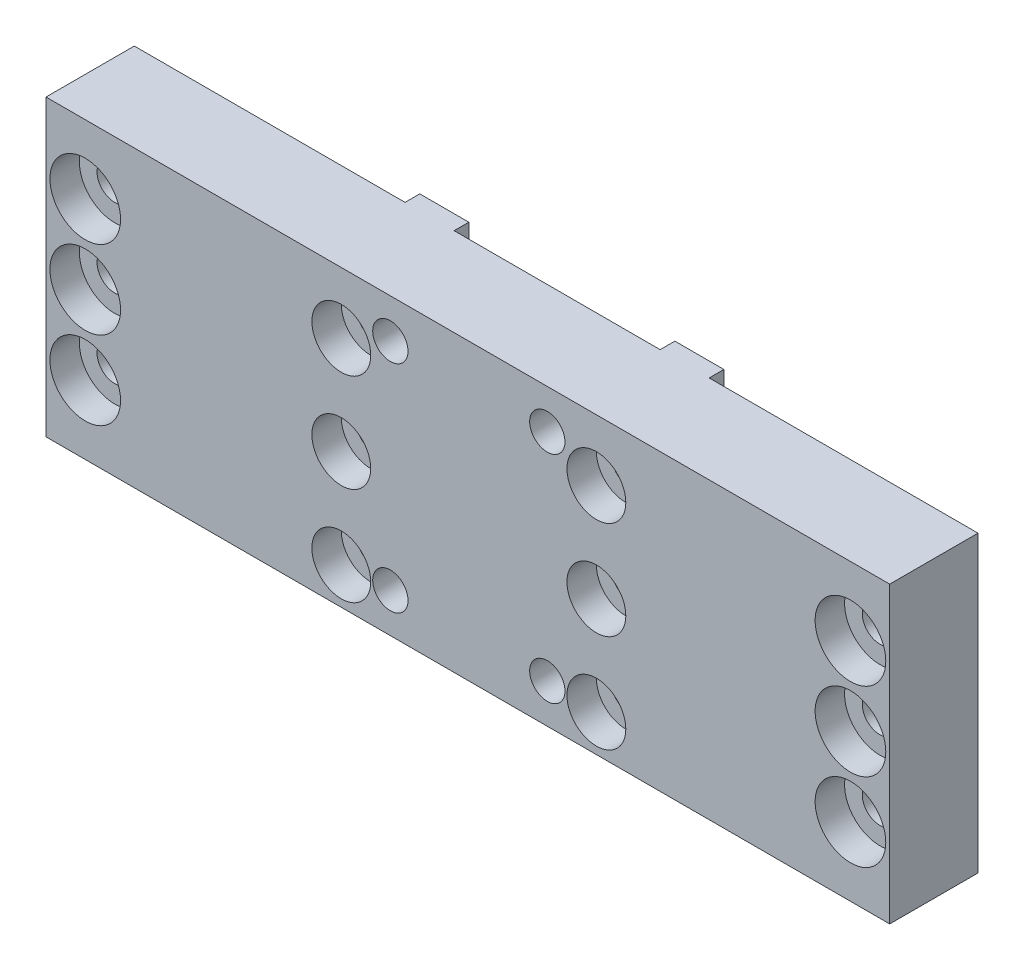
SolidWorks part; units mm, degrees
material "ABS"
ref_plane "前基準面" through (0, 0, 0) normal (0, 0, 1) x (1, 0, 0)
ref_plane "上基準面" through (0, 0, 0) normal (0, 1, 0) x (1, 0, 0)
ref_plane "右基準面" through (0, 0, 0) normal (1, 0, 0) x (0, 0, -1)
sketch "草圖1" plane through (0, 0, 0) normal (0, 0, 1) x (1, 0, 0)
  line L1 (0, 0) -> (70, 0)
  line L2 (0, 0) -> (0, 30)
  line L3 (0, 30) -> (70, 30)
  line L4 (70, 0) -> (70, 30)
  dimension "D1" = 70
  dimension "D2" = 30
extrude "填料-伸長1" add sketch "草圖1" along normal blind 9
sketch "草圖2" plane through (0, 0, 0) normal (-1, 0, 0) x (0, 0, 1)
  line L0 (9, 30) -> (9, 0) construction
  line L1 (9, 30) -> (-103.1, 30)
  line L2 (9, 30) -> (9, 0)
  line L3 (9, 0) -> (-103.1, 0)
  line L4 (-103.1, 30) -> (-103.1, 0)
  dimension "D1" = 30
  dimension "D2" = 112.1
extrude "填料-伸長2" add sketch "草圖2" along normal blind 8
sketch "草圖3" plane through (70, 0, 0) normal (1, 0, 0) x (0, 0, -1)
  line L5 (-9, 30) -> (33.6, 30)
  line L6 (-9, 30) -> (-9, 0)
  line L7 (-9, 0) -> (33.6, 0)
  line L8 (33.6, 30) -> (33.6, 0)
  dimension "D1" = 42.6
extrude "填料-伸長3" add sketch "草圖3" along normal blind 8
sketch "草圖5" plane through (0, 0, -33.6) normal (0, 0, -1) x (-1, 0, 0)
  line L5 (-78, 30) -> (-59.5, 30)
  line L6 (-78, 30) -> (-78, 0)
  line L11 (-78, 0) -> (-59.5, 0)
  line L12 (-59.5, 30) -> (-59.5, 0)
  circle A6 centre (-65.75, 26) radius 2
  circle A7 centre (-65.75, 18) radius 2
  circle A8 centre (-65.75, 10) radius 2
  dimension "D3" = 8
  dimension "D1" = 18.5
  dimension "D2" = 30
  dimension "D4" = 8
  dimension "D5" = 10
  dimension "D6" = 6.25
  dimension "D7" = 6.25
  dimension "D8" = 6.25
extrude "填料-伸長4" add sketch "草圖5" along normal blind 5.5
sketch "草圖11" plane through (-8, 0, 0) normal (-1, 0, 0) x (0, 0, 1)
  line L0 (9, 30) -> (-103.1, 30) construction
  line L2 (9, 0) -> (9, 30) construction
  circle A0 centre (-23, 23) radius 2
  circle A1 centre (-23, 15) radius 2
  circle A2 centre (-23, 7) radius 2
  circle A3 centre (-15, 23) radius 2
  circle A4 centre (-15, 15) radius 2
  circle A5 centre (-15, 7) radius 2
  circle A6 centre (-7, 23) radius 2
  circle A7 centre (-7, 15) radius 2
  circle A8 centre (-7, 7) radius 2
  dimension "D1" = 8
  dimension "D6" = 4
  dimension "D2" = 8
  dimension "D3" = 7
  dimension "D4" = 16
  dimension "D5" = 3
extrude "除料-伸長4" cut sketch "草圖11" against normal blind 8
sketch "草圖12" plane through (0, 0, -103.1) normal (0, 0, -1) x (-1, 0, 0)
  line L0 (8, 30) -> (0, 30) construction
  line L2 (0, 30) -> (0, 0) construction
  circle A0 centre (3, 23) radius 1.8
  circle A1 centre (3, 15) radius 1.8
  circle A2 centre (3, 7) radius 1.8
  dimension "D1" = 8
  dimension "D5" = 3.6
  dimension "D6" = 3.6
  dimension "D7" = 3.6
  dimension "D2" = 8
  dimension "D3" = 7
  dimension "D4" = 3
extrude "除料-伸長6" cut sketch "草圖12" against normal blind 8
sketch "草圖13" plane through (78, 0, 0) normal (1, 0, 0) x (0, 0, -1)
  line L0 (39.1, 30) -> (39.1, 0) construction
  circle A3 centre (9.1, 23) radius 2
  circle A4 centre (9.1, 15) radius 2
  circle A5 centre (9.1, 7) radius 2
  circle A6 centre (17.1, 23) radius 2
  circle A7 centre (17.1, 15) radius 2
  circle A8 centre (17.1, 7) radius 2
  circle A9 centre (25.1, 23) radius 2
  circle A10 centre (25.1, 15) radius 2
  circle A11 centre (25.1, 7) radius 2
  dimension "D1" = 8
  dimension "D2" = 8
  dimension "D3" = 8
  dimension "D4" = 8
  dimension "D6" = 8
  dimension "D5" = 8
  dimension "D7" = 14
  dimension "D8" = 8
  dimension "D9" = 8
extrude "除料-伸長7" cut sketch "草圖13" against normal blind 8
sketch "草圖14" plane through (-8, 0, 0) normal (-1, 0, 0) x (0, 0, 1)
  line L1 (9, 30) -> (-103.1, 30) construction
  line L2 (-103.1, 30) -> (-103.1, 0) construction
  circle A0 centre (-85.1, 23) radius 2
  circle A1 centre (-85.1, 15) radius 2
  circle A2 centre (-85.1, 7) radius 2
  circle A3 centre (-77.1, 23) radius 2
  circle A4 centre (-77.1, 15) radius 2
  circle A5 centre (-77.1, 7) radius 2
  circle A6 centre (-69.1, 23) radius 2
  circle A7 centre (-69.1, 15) radius 2
  circle A8 centre (-69.1, 7) radius 2
  circle A9 centre (-61.1, 23) radius 2
  circle A10 centre (-61.1, 15) radius 2
  circle A11 centre (-61.1, 7) radius 2
  dimension "D1" = 8
  dimension "D6" = 4
  dimension "D2" = 8
  dimension "D3" = 7
  dimension "D5" = 18
  dimension "D4" = 4
extrude "除料-伸長8" cut sketch "草圖14" against normal blind 10
sketch "草圖19" plane through (0, 30, 0) normal (0, 1, 0) x (1, 0, 0)
  line L3 (19.6, 0) -> (24.6, 0)
  line L8 (45.6, 0) -> (50.6, 0)
  line L10 (19.6, 0) -> (19.6, -9)
  line L11 (78, -9) -> (-8, -9) construction
  line L12 (19.6, -9) -> (24.6, -9)
  line L13 (24.6, -9) -> (24.6, 0)
  line L14 (45.6, 0) -> (45.6, -9)
  line L15 (45.6, -9) -> (50.6, -9)
  line L16 (50.6, -9) -> (50.6, 0)
  dimension "D1" = 5
  dimension "D2" = 5
  dimension "D3" = 21
  dimension "D4" = 9
  dimension "D5" = 9
extrude "填料-伸長6" add sketch "草圖19" against normal blind 36.25
sketch "草圖20" plane through (0, 0, 0) normal (0, 0, -1) x (-1, 0, 0)
  line L0 (-70, 30) -> (0, 30) construction
  line L13 (-50.6, 30) -> (-45.6, 30)
  line L18 (-50.6, 30) -> (-50.6, 36.25)
  line L19 (-50.6, 36.25) -> (-45.6, 36.25)
  line L20 (-45.6, 30) -> (-45.6, 36.25)
  line L22 (-24.6, 30) -> (-19.6, 30)
  line L23 (-24.6, 30) -> (-24.6, 36.25)
  line L24 (-24.6, 36.25) -> (-19.6, 36.25)
  line L25 (-19.6, 30) -> (-19.6, 36.25)
  dimension "D1" = 5
  dimension "D2" = 6.25
  dimension "D3" = 19.4
  dimension "D4" = 21
  dimension "D5" = 5
  dimension "D6" = 6.25
extrude "填料-伸長7" add sketch "草圖20" against normal blind 9
sketch "草圖21" plane through (0, 0, 0) normal (0, 0, -1) x (-1, 0, 0)
  line L0 (-50.6, -6.25) -> (-45.6, -6.25) construction
  line L1 (-24.6, -6.25) -> (-19.6, -6.25) construction
  circle A1 centre (-48.1, 23.75) radius 1.3
  circle A2 centre (-48.1, 13.75) radius 1.3
  circle A3 centre (-48.1, 3.75) radius 1.3
  circle A4 centre (-22.1, 23.75) radius 1.3
  circle A5 centre (-22.1, 13.75) radius 1.3
  circle A6 centre (-22.1, 3.75) radius 1.3
  dimension "D1" = 2.6
  dimension "D2" = 2.6
  dimension "D3" = 2.6
  dimension "D4" = 2.6
  dimension "D5" = 2.6
  dimension "D6" = 2.6
  dimension "D7" = 10
  dimension "D8" = 10
  dimension "D9" = 10
  dimension "D10" = 10
  dimension "D11" = 10
  dimension "D12" = 10
extrude "除料-伸長10" cut sketch "草圖21" against normal blind 9
sketch "草圖25" plane through (0, 36.25, 0) normal (0, 1, 0) x (1, 0, 0)
  line L1 (19.6, 0) -> (24.6, 0)
  line L2 (19.6, 0) -> (19.6, 1.5)
  line L3 (19.6, 1.5) -> (24.6, 1.5)
  line L4 (24.6, 0) -> (24.6, 1.5)
  line L5 (45.6, 0) -> (50.6, 0)
  line L6 (45.6, 0) -> (45.6, 1.5)
  line L7 (45.6, 1.5) -> (50.6, 1.5)
  line L8 (50.6, 0) -> (50.6, 1.5)
  dimension "D1" = 1.5
  dimension "D2" = 1.5
  dimension "D3" = 5
  dimension "D4" = 5
extrude "填料-伸長8" add sketch "草圖25" against normal blind 42.5
sketch "草圖26" plane through (0, 0, -1.5) normal (0, 0, -1) x (-1, 0, 0)
  line L0 (-50.6, -6.25) -> (-50.6, 36.25) construction
  line L4 (-50.6, -6.25) -> (-45.6, -6.25) construction
  line L5 (-24.6, -6.25) -> (-19.6, -6.25) construction
  line L6 (-24.6, -6.25) -> (-24.6, 36.25) construction
  circle A0 centre (-48.1, 23.75) radius 1.3
  circle A1 centre (-48.1, 13.75) radius 1.3
  circle A2 centre (-48.1, 3.75) radius 1.3
  circle A3 centre (-22.1, 23.75) radius 1.3
  circle A4 centre (-22.1, 13.75) radius 1.3
  circle A5 centre (-22.1, 3.75) radius 1.3
  dimension "D1" = 2.6
  dimension "D2" = 2.6
  dimension "D3" = 2.6
  dimension "D4" = 2.6
  dimension "D5" = 2.6
  dimension "D6" = 2.6
  dimension "D7" = 2.5
  dimension "D8" = 10
  dimension "D9" = 10
  dimension "D10" = 10
  dimension "D11" = 10
  dimension "D12" = 10
  dimension "D13" = 10
  dimension "D14" = 2.5
extrude "除料-伸長14" cut sketch "草圖26" against normal blind 1.5
sketch "草圖27" plane through (0, 0, 9) normal (0, 0, 1) x (1, 0, 0)
  line L1 (19.6, 36.25) -> (24.6, 36.25)
  line L2 (19.6, 36.25) -> (19.6, 30)
  line L3 (19.6, 30) -> (24.6, 30)
  line L4 (24.6, 36.25) -> (24.6, 30)
  line L5 (45.6, 36.25) -> (50.6, 36.25)
  line L6 (45.6, 36.25) -> (45.6, 30)
  line L7 (45.6, 30) -> (50.6, 30)
  line L8 (50.6, 36.25) -> (50.6, 30)
  line L9 (19.6, 0) -> (24.6, 0)
  line L10 (19.6, 0) -> (19.6, -6.25)
  line L11 (19.6, -6.25) -> (24.6, -6.25)
  line L12 (24.6, 0) -> (24.6, -6.25)
  line L13 (45.6, 0) -> (50.6, 0)
  line L14 (45.6, 0) -> (45.6, -6.25)
  line L15 (45.6, -6.25) -> (50.6, -6.25)
  line L16 (50.6, 0) -> (50.6, -6.25)
extrude "除料-伸長15" cut sketch "草圖27" against normal blind 11
sketch "草圖28" plane through (0, 0, 9) normal (0, 0, 1) x (1, 0, 0)
  circle A0 centre (22.1, 23.75) radius 3
  circle A1 centre (22.1, 13.75) radius 3
  circle A2 centre (22.1, 3.75) radius 3
  circle A3 centre (48.1, 13.75) radius 3
  circle A4 centre (48.1, 3.75) radius 3
  circle A5 centre (48.1, 23.75) radius 3
  dimension "D1" = 6
  dimension "D2" = 6
  dimension "D3" = 6
  dimension "D4" = 6
  dimension "D5" = 6
  dimension "D6" = 6
extrude "除料-伸長16" cut sketch "草圖28" against normal blind 3
sketch "草圖29" plane through (0, 30, 0) normal (0, 1, 0) x (1, 0, 0)
  line L0 (59.5, 39.1) -> (59.5, 33.6) construction
  line L1 (0, 0) -> (-8, 0)
  line L2 (0, 0) -> (0, 103.1)
  line L3 (0, 103.1) -> (-8, 103.1)
  line L4 (-8, 0) -> (-8, 103.1)
  line L5 (70, 0) -> (78, 0)
  line L6 (70, 0) -> (70, 39.1)
  line L7 (70, 39.1) -> (78, 39.1)
  line L8 (78, 0) -> (78, 39.1)
  line L9 (70, 39.1) -> (59.5, 39.1)
  line L10 (70, 39.1) -> (70, 33.6)
  line L11 (70, 33.6) -> (59.5, 33.6)
  line L12 (59.5, 39.1) -> (59.5, 33.6)
  line M1 (-8, 103.1) -> (-8, -9)
  line M3 (78, -9) -> (78, 39.1)
  line M4 (78, 39.1) -> (59.5, 39.1)
  line M5 (59.5, 39.1) -> (59.5, 33.6)
  line M6 (59.5, 33.6) -> (70, 33.6)
  line M7 (70, 33.6) -> (70, 0)
  line M17 (0, 0) -> (0, 103.1)
  line M18 (0, 103.1) -> (-8, 103.1)
extrude "除料-伸長17" cut sketch "草圖29" against normal blind 30 contours L1 M17 M18 M1 | L6 M6 M4 M5 | L6 L5 M7 M3 M4
sketch "草圖30" plane through (0, 0, 9) normal (0, 0, 1) x (1, 0, 0)
  line L0 (78, 30) -> (-8, 30) construction
  line L1 (-8, 0) -> (-8, 30) construction
  circle A0 centre (-4, 23) radius 1.8
  circle A1 centre (-4, 15) radius 1.8
  circle A2 centre (-4, 7) radius 1.8
  dimension "D1" = 8
  dimension "D3" = 3.6
  dimension "D2" = 8
  dimension "D4" = 7
  dimension "D5" = 4
extrude "除料-伸長18" cut sketch "草圖30" against normal blind 10
sketch "草圖31" plane through (0, 0, 9) normal (0, 0, 1) x (1, 0, 0)
  circle A0 centre (-4, 15) radius 3.6
  circle A1 centre (-4, 7) radius 3.6
  circle A2 centre (-4, 23) radius 3.6
  dimension "D1" = 7.2
extrude "除料-伸長19" cut sketch "草圖31" against normal blind 3
sketch "草圖32" plane through (0, 0, 9) normal (0, 0, 1) x (1, 0, 0)
  line L0 (-8, 0) -> (78, 0) construction
  line L1 (78, 30) -> (78, 0) construction
  circle A0 centre (74, 23) radius 1.8
  circle A1 centre (74, 15) radius 1.8
  circle A2 centre (74, 7) radius 1.8
  dimension "D5" = 3.6
  dimension "D1" = 8
  dimension "D2" = 8
  dimension "D3" = 7
  dimension "D4" = 4
extrude "除料-伸長20" cut sketch "草圖32" against normal blind 10
sketch "草圖33" plane through (0, 0, 9) normal (0, 0, 1) x (1, 0, 0)
  circle A0 centre (74, 23) radius 3.6
  circle A1 centre (74, 15) radius 3.6
  circle A2 centre (74, 7) radius 3.6
  dimension "D1" = 7.2
extrude "除料-伸長21" cut sketch "草圖33" against normal blind 3
sketch "草圖35" plane through (0, 0, 0) normal (0, 0, -1) x (-1, 0, 0)
  line L0 (-45.6, 0) -> (-45.6, 30) construction
  line L1 (-24.6, 0) -> (-45.6, 0) construction
  circle A0 centre (-43.1, 4) radius 1.8
  circle A1 centre (-43.1, 26) radius 1.8
  circle A2 centre (-27.1, 26) radius 1.8
  circle A3 centre (-27.1, 4) radius 1.8
  dimension "D1" = 3.6
  dimension "D2" = 2.5
  dimension "D3" = 4
  dimension "D4" = 2
  dimension "D5" = 2
extrude "除料-伸長22" cut sketch "草圖35" against normal up to next
